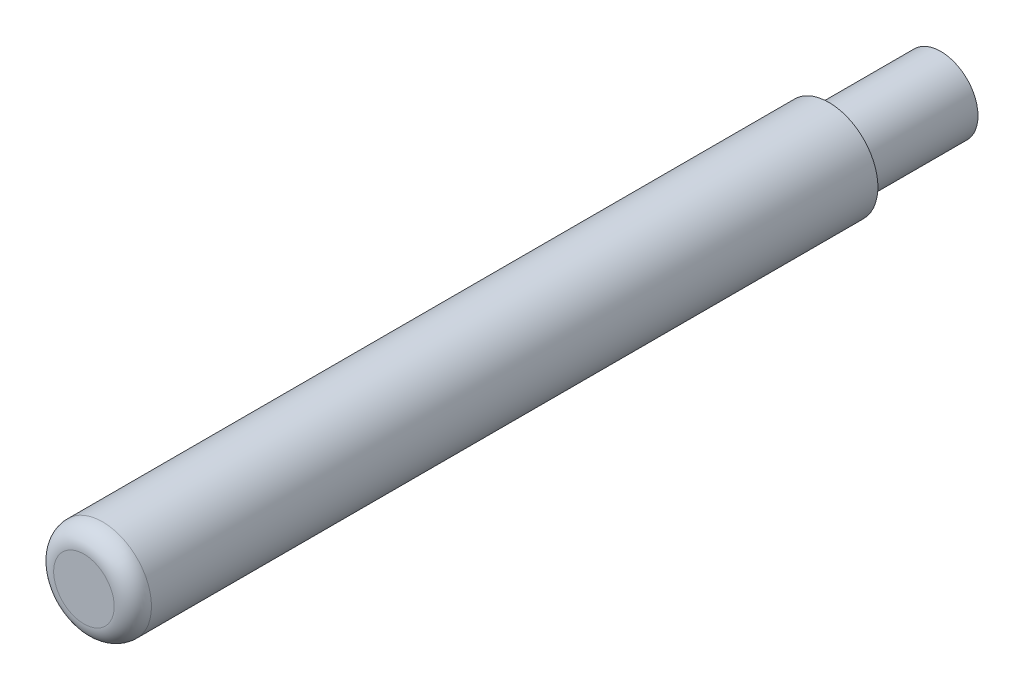
SolidWorks part; units mm, degrees
material "PET"
ref_plane "Front Plane" through (0, 0, 0) normal (0, 0, 1) x (1, 0, 0)
ref_plane "Top Plane" through (0, 0, 0) normal (0, 1, 0) x (1, 0, 0)
ref_plane "Right Plane" through (0, 0, 0) normal (1, 0, 0) x (0, 0, -1)
sketch "Sketch1" plane through (0, 0, 0) normal (0, 0, 1) x (1, 0, 0)
  circle A0 centre (0, 0) radius 5.08
  dimension "D1" = 10.16
extrude "Boss-Extrude1" add sketch "Sketch1" against normal blind 15.24
sketch "Sketch2" plane through (0, 0, 0) normal (0, 0, 1) x (1, 0, 0)
  circle A0 centre (0, 0) radius 6.6675
  dimension "D1" = 13.335
extrude "Boss-Extrude2" add sketch "Sketch2" along normal blind 101.6
fillet "Fillet1" radius 2.54 1 edges at (6.6675, 0, 101.6)
